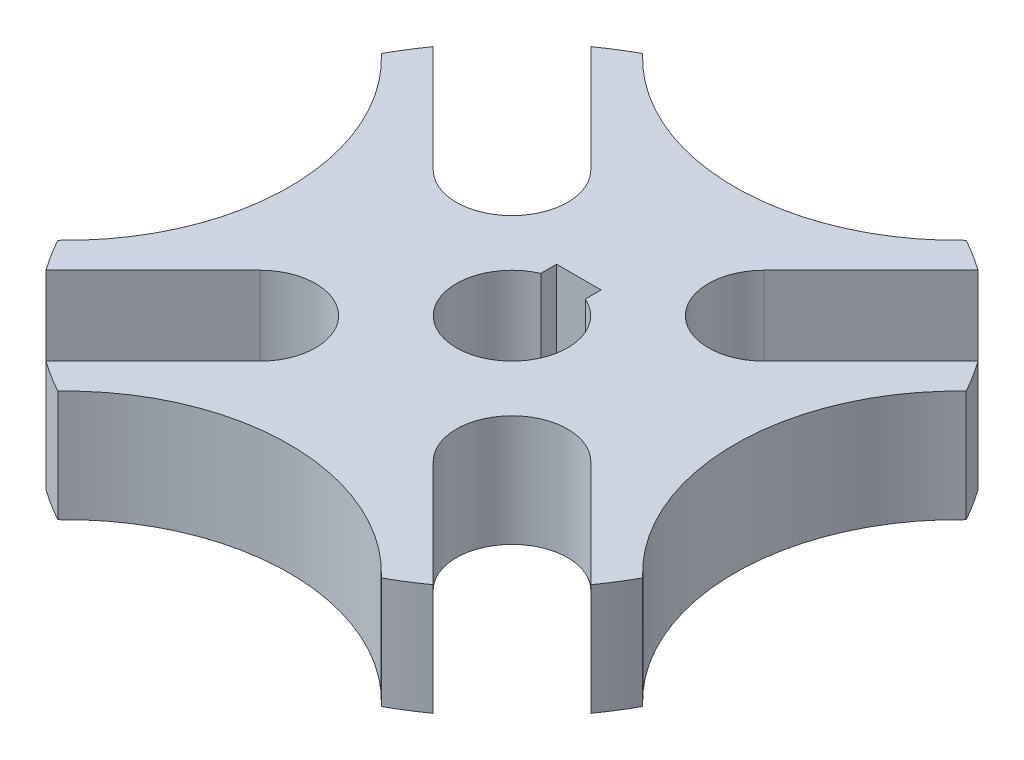
SolidWorks part; units mm, degrees
ref_plane "前视基准面" through (0, 0, 0) normal (0, 0, 1) x (1, 0, 0)
ref_plane "上视基准面" through (0, 0, 0) normal (0, 1, 0) x (1, 0, 0)
ref_plane "右视基准面" through (0, 0, 0) normal (1, 0, 0) x (0, 0, -1)
other "Configuration Table"
sketch "草图1" plane through (0, 0, 0) normal (0, 1, 0) x (1, 0, 0)
  circle A0 centre (0, 0) radius 15
  circle A1 centre (0, 0) radius 2.5
  dimension "D1" = 30
  dimension "D2" = 5
extrude "凸台-拉伸1" add sketch "草图1" along normal blind 5
sketch "草图2" plane through (0, 5, 0) normal (0, 1, 0) x (1, 0, 0)
  line L1 (-1, 3) -> (1, 3)
  line L2 (-1, 3) -> (-1, 2)
  line L3 (-1, 2) -> (1, 2)
  line L4 (1, 3) -> (1, 2)
  line L5 (-1, 3) -> (1, 2) construction
  line L6 (-1, 2) -> (1, 3) construction
  circle A0 centre (0, 0) radius 2.5 construction
  point P0 (0, 2.5)
  dimension "D1" = 2
  dimension "D2" = 1
extrude "切除-拉伸1" cut sketch "草图2" against normal blind 10
sketch "草图3" plane through (0, 5, 0) normal (0, 1, 0) x (1, 0, 0)
  line L0 (0, 20) -> (0, -20) construction
  circle A1 centre (0, 20) radius 10
  circle A2 centre (20, 0) radius 10
  circle A3 centre (0, -20) radius 10
  circle A4 centre (-20, 0) radius 10
  point P2 (0, 0)
  dimension "D2" = 20
  dimension "D1" = 40
  dimension "D3" = 4
extrude "切除-拉伸2" cut sketch "草图3" against normal blind 10
sketch "草图4" plane through (0, 5, 0) normal (0, 1, 0) x (1, 0, 0)
  line L0 (-10.8722, 10.8722) -> (10.6066, -10.6066) construction
  line L1 (-12.6399, 9.1044) -> (-7.4246, 3.8891)
  line L2 (-9.1044, 12.6399) -> (-3.8891, 7.4246)
  line L3 (-12.6399, 9.1044) -> (-9.1044, 12.6399)
  line L4 (-12.6399, 9.1044) -> (8.8388, -12.3744) construction
  line L5 (-9.1044, 12.6399) -> (12.3744, -8.8388) construction
  line L6 (12.6399, 9.1044) -> (7.4246, 3.8891)
  line L7 (9.1044, 12.6399) -> (3.8891, 7.4246)
  line L8 (9.1044, 12.6399) -> (12.6399, 9.1044)
  line L9 (9.1044, -12.6399) -> (3.8891, -7.4246)
  line L10 (12.6399, -9.1044) -> (7.4246, -3.8891)
  line L11 (12.6399, -9.1044) -> (9.1044, -12.6399)
  line L12 (-12.6399, -9.1044) -> (-7.4246, -3.8891)
  line L13 (-9.1044, -12.6399) -> (-3.8891, -7.4246)
  line L14 (-9.1044, -12.6399) -> (-12.6399, -9.1044)
  arc A1 (7.2618, -13.125) -> (13.125, -7.2618) centre (0, 0) ccw construction
  arc A2 (-7.4246, 3.8891) -> (-3.8891, 7.4246) centre (-5.6569, 5.6569) ccw
  arc A3 (3.8891, 7.4246) -> (7.4246, 3.8891) centre (5.6569, 5.6569) ccw
  arc A4 (7.4246, -3.8891) -> (3.8891, -7.4246) centre (5.6569, -5.6569) ccw
  arc A5 (-3.8891, -7.4246) -> (-7.4246, -3.8891) centre (-5.6569, -5.6569) ccw
  dimension "D1" = 5
  dimension "D2" = 8
  dimension "D3" = 2.5
  dimension "D4" = 2.5
  dimension "D5" = 4
extrude "切除-拉伸3" cut sketch "草图4" against normal blind 10
